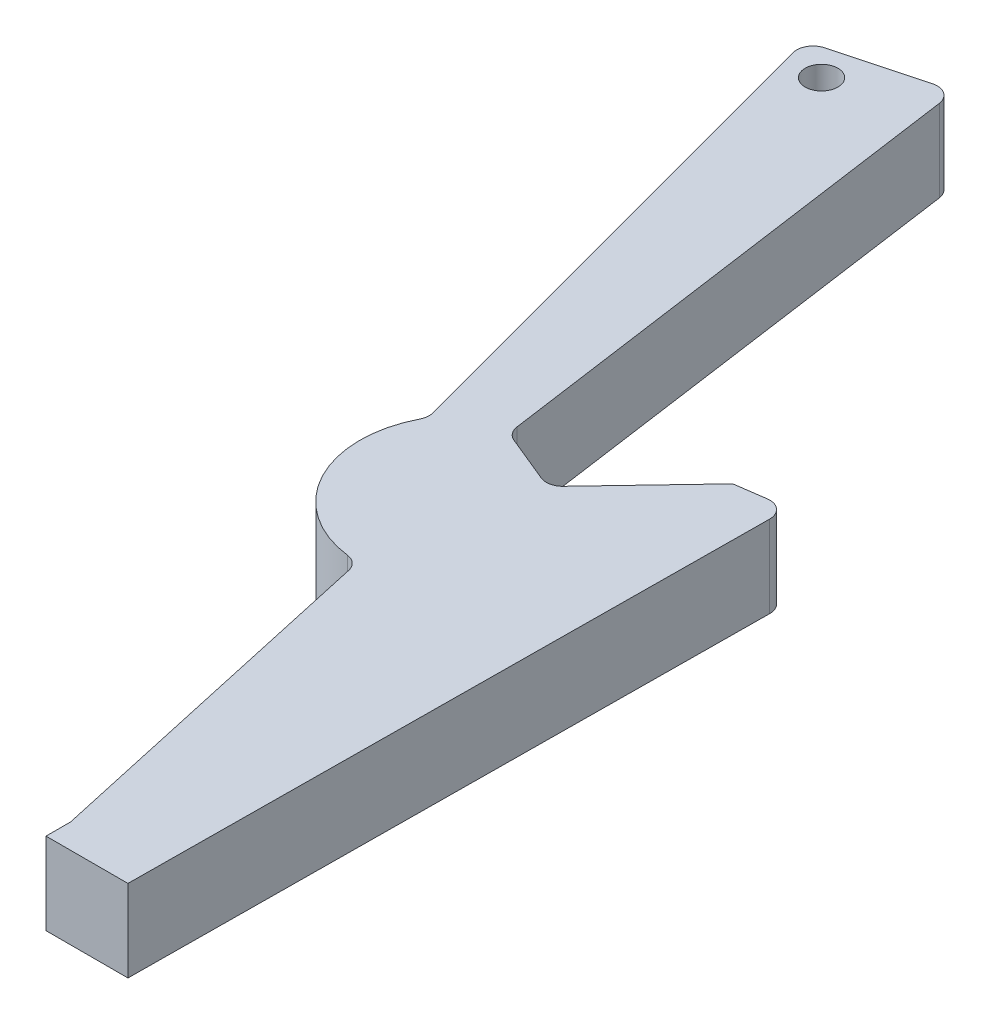
SolidWorks part; units mm, degrees
ref_plane "Front Plane" through (0, 0, 0) normal (0, 0, 1) x (1, 0, 0)
ref_plane "Top Plane" through (0, 0, 0) normal (0, 1, 0) x (1, 0, 0)
ref_plane "Right Plane" through (0, 0, 0) normal (1, 0, 0) x (0, 0, -1)
sketch "Sketch1" plane through (0, 0, 0) normal (0, 1, 0) x (1, 0, 0)
  line L0 (-65.0411, 76.5879) -> (53.5466, 76.5879) construction
  line L1 (23.8997, 76.5879) -> (9.4108, 72.7056)
  line L2 (9.4108, 72.7056) -> (26.2341, 9.9204)
  line L3 (23.8997, 76.5879) -> (32.8068, 13.2107)
  line L4 (32.8068, 13.2107) -> (40.8068, 9.9204)
  line L5 (40.8068, 9.9204) -> (51.829, 21.5183)
  line L6 (51.829, 21.5183) -> (57.829, 22.3616)
  line L7 (57.829, 22.3616) -> (57.1559, -57.6384)
  line L8 (57.1559, -57.6384) -> (47.1559, -57.6384)
  line L9 (47.1559, -57.6384) -> (47.1559, -54.6384)
  line L10 (47.1559, -54.6384) -> (37.2215, -9.6384)
  arc A0 (26.2341, 9.9204) -> (37.2215, -9.6384) centre (37.4569, 3.3594) ccw
  dimension "D11" = 13
  dimension "D1" = 15
  dimension "D2" = 15
  dimension "D3" = 90
  dimension "D4" = 65
  dimension "D5" = 83
  dimension "D6" = 64
  dimension "D7" = 8
  dimension "D8" = 16
  dimension "D9" = 6
  dimension "D10" = 80
  dimension "D12" = 45
  dimension "D13" = 10
  dimension "D14" = 3
extrude "Boss-Extrude1" add sketch "Sketch1" along normal blind 10
sketch "Sketch2" plane through (0, 10, 0) normal (0, 1, 0) x (1, 0, 0)
  line L0 (23.8997, 76.5879) -> (9.4108, 72.7056) construction
  line L1 (9.4108, 72.7056) -> (26.2341, 9.9204) construction
  circle A0 centre (14.3098, 69.8772) radius 2
  dimension "D1" = 4
  dimension "D2" = 4
  dimension "D3" = 4
extrude "Cut-Extrude1" cut sketch "Sketch2" against normal through all
fillet "Fillet1" radius 2 7 edges at (26.2341, 5, -9.9204) (37.2215, 5, 9.6384) (40.8068, 5, -9.9204) (32.8068, 5, -13.2107) (57.829, 5, -22.3616) (23.8997, 5, -76.5879) (9.4108, 5, -72.7056)
